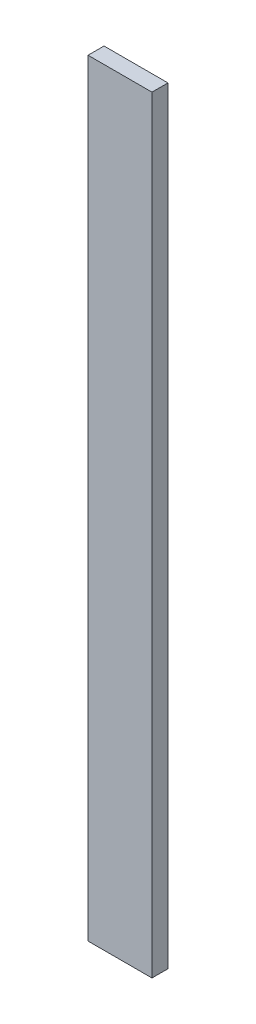
SolidWorks part; units mm, degrees
material "Pin"
ref_plane "Front" through (0, 0, 0) normal (0, 0, 1) x (1, 0, 0)
ref_plane "Top" through (0, 0, 0) normal (0, 1, 0) x (1, 0, 0)
ref_plane "Right" through (0, 0, 0) normal (1, 0, 0) x (0, 0, -1)
sketch "Esquisse1" plane through (0, 0, 0) normal (0, 0, 1) x (1, 0, 0)
  line L1 (-12.7, 152.4) -> (12.7, 152.4)
  line L2 (-12.7, 152.4) -> (-12.7, -152.4)
  line L3 (-12.7, -152.4) -> (12.7, -152.4)
  line L4 (12.7, 152.4) -> (12.7, -152.4)
  line L5 (-12.7, 152.4) -> (12.7, -152.4) construction
  line L6 (-12.7, -152.4) -> (12.7, 152.4) construction
  point P0 (0, 0)
  dimension "D1" = 304.8
  dimension "D2" = 25.4
extrude "Boss.-Extru.1" add sketch "Esquisse1" along normal blind 6.35
